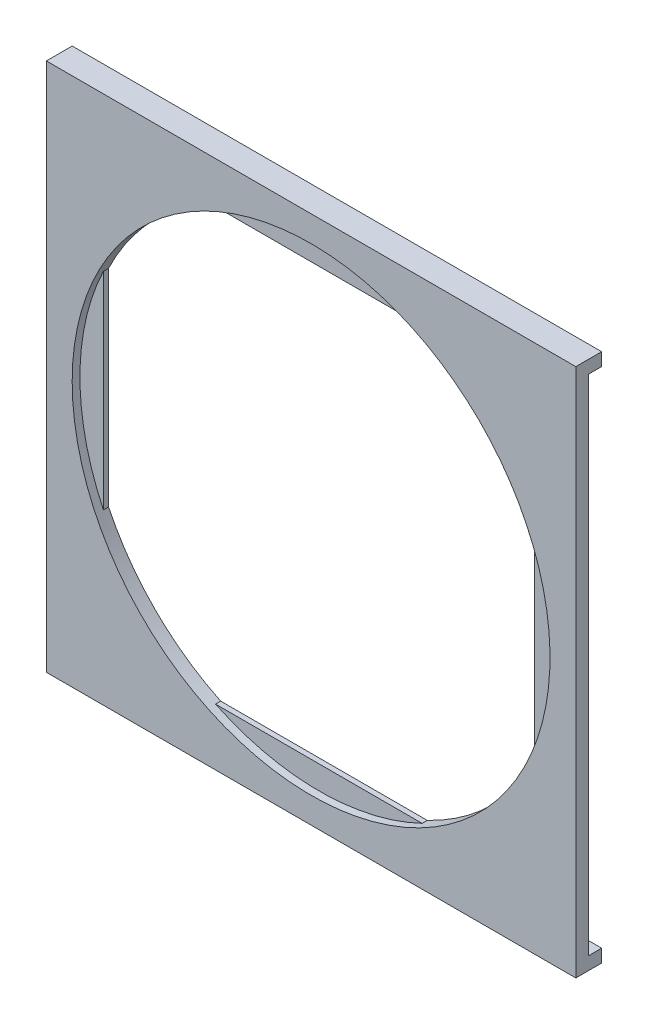
SolidWorks part; units mm, degrees
ref_plane "前视基准面" through (0, 0, 0) normal (0, 0, 1) x (1, 0, 0)
ref_plane "上视基准面" through (0, 0, 0) normal (0, 1, 0) x (1, 0, 0)
ref_plane "右视基准面" through (0, 0, 0) normal (1, 0, 0) x (0, 0, -1)
sketch "草图7" plane through (0, 0, 0) normal (0, 0, 1) x (1, 0, 0)
  line L1 (0, 0) -> (400, 0)
  line L2 (0, 0) -> (0, 400)
  line L3 (0, 400) -> (400, 400)
  line L4 (400, 0) -> (400, 400)
  dimension "D1" = 400
  dimension "D2" = 400
extrude "凸台-拉伸1" add sketch "草图7" along normal blind 3
sketch "草图8" plane through (0, 0, 3) normal (0, 0, 1) x (1, 0, 0)
  line L0 (10, 390) -> (390, 390)
  line L1 (400, 0) -> (400, 400) construction
  line L2 (0, 400) -> (0, 0) construction
  line L3 (400, 400) -> (0, 400) construction
  line L4 (10, 390) -> (10, 388)
  line L5 (10, 388) -> (390, 388)
  line L6 (390, 388) -> (390, 390)
  dimension "D1" = 10
  dimension "D2" = 10
  dimension "D3" = 10
  dimension "D4" = 2
extrude "凸台-拉伸2" add sketch "草图8" along normal blind 140
sketch "草图9" plane through (0, 0, 3) normal (0, 0, 1) x (1, 0, 0)
  line L1 (10, 390) -> (12, 390)
  line L2 (10, 390) -> (10, 8)
  line L3 (10, 8) -> (12, 8)
  line L4 (12, 390) -> (12, 8)
  dimension "D1" = 2
  dimension "D2" = 382
extrude "凸台-拉伸3" add sketch "草图9" along normal blind 140
pattern_linear "阵列(线性)1" count 12 spacing 30 along (1, 0, 0) of "凸台-拉伸3"
pattern_linear "阵列(线性)3" count 12 spacing 30 along (0, -1, 0) of "凸台-拉伸2"
sketch "草图11" plane through (0, 0, 0) normal (0, 0, -1) x (-1, 0, 0)
  line L4 (0, 0) -> (0, 400)
  line L5 (0, 0) -> (0, 400)
  line L6 (0, 400) -> (-400, 400)
  line L7 (0, 400) -> (-400, 400)
  line L12 (-400, 400) -> (-400, 0)
  line L13 (-400, 400) -> (-400, 0)
  line L14 (-400, 0) -> (0, 0)
  line L15 (-400, 0) -> (0, 0)
  dimension "D1" = 0
extrude "切除-拉伸1" cut sketch "草图11" against normal blind 3
sketch "草图12" plane through (0, 0, 3) normal (0, 0, -1) x (-1, 0, 0)
  line L0 (-190, 238) -> (-190, 210) construction
  circle A0 centre (-191, 208.9584) radius 90
  circle A1 centre (-191, 208.9584) radius 300
  dimension "D2" = 180
  dimension "D3" = 600
  dimension "D1" = 1
extrude "切除-拉伸2" cut sketch "草图12" against normal through all both and the other way through all
sketch "草图13" plane through (0, 0, 3) normal (0, 0, -1) x (-1, 0, 0)
  line L0 (-190, 238) -> (-190, 210) construction
  line L1 (-162, 208) -> (-190, 208) construction
  circle A0 centre (-191, 209) radius 89.5
  circle A1 centre (-191, 209) radius 92.5
  dimension "D4" = 179
  dimension "D1" = 1
  dimension "D2" = 1
  dimension "D3" = 3
extrude "凸台-拉伸8" add sketch "草图13" against normal up to surface (140 mm away) up to face at (236, 254, 143)
sketch "草图14" plane through (0, 0, 3) normal (0, 0, -1) x (-1, 0, 0)
  line L0 (-293.5, 106.5) -> (-293.5, 311.5)
  line L5 (-293.5, 311.5) -> (-88.5, 311.5)
  line L6 (-88.5, 106.5) -> (-88.5, 311.5)
  line L7 (-283.5, 116.5) -> (-283.5, 301.5)
  line L8 (-293.5, 106.5) -> (-88.5, 106.5)
  line L9 (-283.5, 301.5) -> (-98.5, 301.5)
  line L10 (-98.5, 116.5) -> (-98.5, 301.5)
  line L11 (-283.5, 116.5) -> (-98.5, 116.5)
  circle A2 centre (-191, 209) radius 92.5 construction
  circle A3 centre (-191, 209) radius 92.5
  dimension "D1" = 10
extrude "凸台-拉伸9" add sketch "草图14" along normal blind 5 separate body contours L0 L8 L6 L5 L11 L7 L9 L10 | A3 L7 L11 | A3 L9 L7 | A3 L10 L9 | A3 L11 L10
sketch "草图15" plane through (0, 0, -2) normal (0, 0, -1) x (-1, 0, 0)
  line L0 (-231, 292.4041) -> (-151, 292.4041)
  circle A1 centre (-191, 209) radius 92.5
  arc A3 (-151, 292.4041) -> (-231, 292.4041) centre (-191, 209) ccw
  dimension "D2" = 80
  dimension "D1" = 0
extrude "凸台-拉伸10" add sketch "草图15" against normal blind 2
pattern_circular "阵列(圆周)1" count 4 over 360 about axis through (191, 209, 0) along (0, 0, 1) of "凸台-拉伸10"
sketch "草图16" plane through (0, 0, 143) normal (0, 0, 1) x (1, 0, 0)
  circle A1 centre (191, 209) radius 92.5
  circle A2 centre (191, 209) radius 92.5
  dimension "D1" = 0
extrude "切除-拉伸3" cut sketch "草图16" against normal up to surface (140 mm away) up to face at (98.5, 209, 3)
sketch "草图17" plane through (0, 0, -2) normal (0, 0, -1) x (-1, 0, 0)
  line L0 (-88.5, 106.5) -> (-88.5, 311.5) construction
  line L1 (-293.5, 311.5) -> (-88.5, 311.5)
  line L2 (-293.5, 311.5) -> (-293.5, 306.5)
  line L3 (-293.5, 306.5) -> (-88.5, 306.5)
  line L4 (-88.5, 311.5) -> (-88.5, 306.5)
  line L5 (-293.5, 106.5) -> (-293.5, 311.5) construction
  line L6 (-88.5, 106.5) -> (-293.5, 106.5)
  line L7 (-88.5, 106.5) -> (-88.5, 111.5)
  line L8 (-88.5, 111.5) -> (-293.5, 111.5)
  line L9 (-293.5, 106.5) -> (-293.5, 111.5)
  dimension "D1" = 5
  dimension "D2" = 5
extrude "凸台-拉伸11" add sketch "草图17" along normal blind 5
